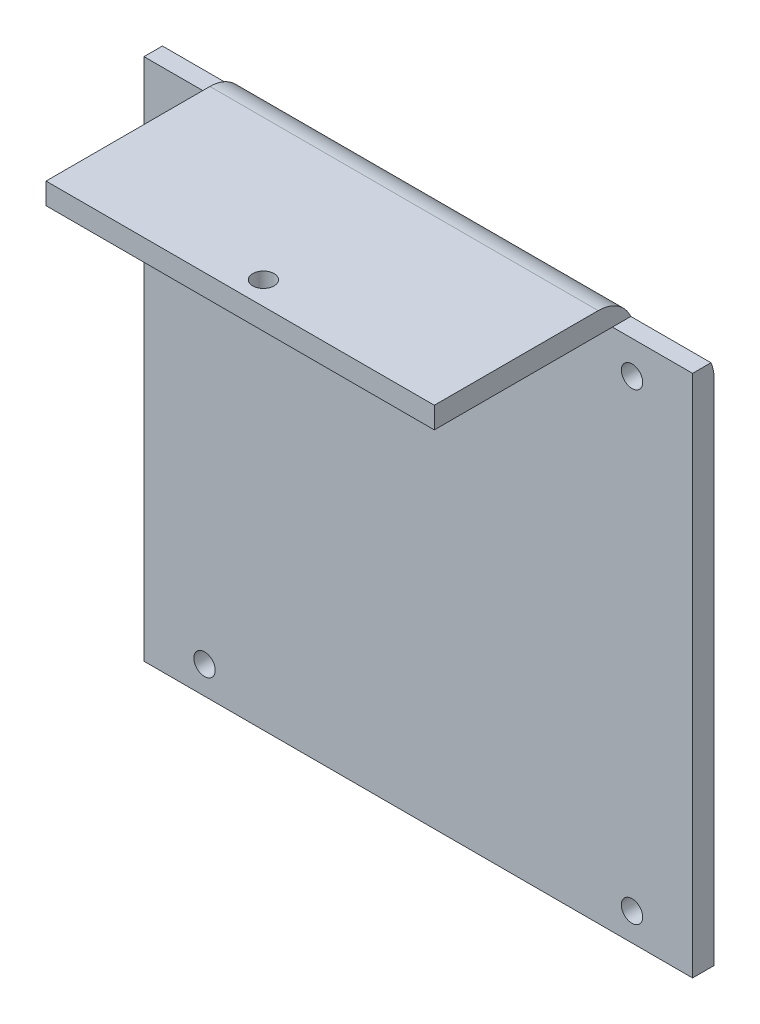
SolidWorks part; units mm, degrees
ref_plane "Plan de face" through (0, 0, 0) normal (0, 0, 1) x (1, 0, 0)
ref_plane "Plan de dessus" through (0, 0, 0) normal (0, 1, 0) x (1, 0, 0)
ref_plane "Plan de droite" through (0, 0, 0) normal (1, 0, 0) x (0, 0, -1)
sketch "Esquisse1" plane through (0, 0, 0) normal (0, 0, 1) x (1, 0, 0)
  line L1 (-38.5, 36.75) -> (38.5, 36.75)
  line L2 (-38.5, 36.75) -> (-38.5, -36.75)
  line L3 (-38.5, -36.75) -> (38.5, -36.75)
  line L4 (38.5, 36.75) -> (38.5, -36.75)
  line L5 (-38.5, 36.75) -> (38.5, -36.75) construction
  line L6 (-38.5, -36.75) -> (38.5, 36.75) construction
  line L7 (30, 32.15) -> (-30, 32.15) construction
  line L8 (30, 32.15) -> (30, -32.85) construction
  line L9 (30, -32.85) -> (-30, -32.85) construction
  line L10 (-30, 32.15) -> (-30, -32.85) construction
  line L11 (30, 32.15) -> (-30, -32.85) construction
  line L12 (30, -32.85) -> (-30, 32.15) construction
  circle A0 centre (30, 32.15) radius 1.5
  circle A1 centre (30, -32.85) radius 1.5
  circle A2 centre (-30, -32.85) radius 1.5
  circle A3 centre (-30, 32.15) radius 1.5
  point P0 (0, 0)
  point P6 (0, 0)
  point P19 (0, -0.35)
  dimension "D3" = 3
  dimension "D1" = 77
  dimension "D2" = 73.5
  dimension "D4" = 65
  dimension "D5" = 60
  dimension "D6" = 3.9
extrude "Boss.-Extru.1" add sketch "Esquisse1" along normal blind 3
sketch "Esquisse9" plane through (0, 36.75, 0) normal (0, 1, 0) x (1, 0, 0)
  line L0 (38.5, 0) -> (-38.5, 0) construction
  line L1 (-27.25, 0) -> (27.25, 0)
  line L2 (-27.25, 0) -> (-27.25, -3)
  line L3 (-27.25, -3) -> (27.25, -3)
  line L4 (27.25, 0) -> (27.25, -3)
  line L5 (38.5, -3) -> (-38.5, -3) construction
  line L6 (-38.5, -3) -> (-38.5, 0) construction
  point P10 (0, 0)
  point P12 (0, 0)
  dimension "D1" = 11.25
sketch "Esquisse45" plane through (0, 36.75, 0) normal (0, 1, 0) x (1, 0, 0)
  line L0 (38.5, 0) -> (-38.5, 0) construction
  line L1 (-27.25, 0) -> (27.25, 0)
  line L2 (-27.25, 0) -> (-27.25, -3)
  line L3 (-27.25, -3) -> (27.25, -3)
  line L4 (27.25, 0) -> (27.25, -3)
  line L5 (38.5, -3) -> (-38.5, -3) construction
  line L6 (-38.5, -3) -> (-38.5, 0) construction
  line L7 (38.5, -3) -> (38.5, 0) construction
  dimension "D1" = 11.25
  dimension "D2" = 11.25
extrude "Boss.-Extru.2" add sketch "Esquisse45" along normal blind 3
sketch "Esquisse46" plane through (0, 0, 3) normal (0, 0, 1) x (1, 0, 0)
  line L1 (-27.25, 39.75) -> (27.25, 39.75)
  line L2 (-27.25, 39.75) -> (-27.25, 36.75)
  line L3 (-27.25, 36.75) -> (27.25, 36.75)
  line L4 (27.25, 39.75) -> (27.25, 36.75)
extrude "Boss.-Extru.3" add sketch "Esquisse46" along normal blind 25
fillet "Congé1" radius 5 1 edges at (0, 39.75, 0)
sketch "Esquisse47" plane through (0, 39.75, 0) normal (0, 1, 0) x (1, 0, 0)
  line L0 (-27.25, -24.7426) -> (27.25, -24.7426) construction
  line L1 (-27.25, -5) -> (-27.25, -28) construction
  line L2 (27.25, -28) -> (27.25, -5) construction
  line L3 (27.25, -5) -> (-27.25, -5) construction
  circle A0 centre (0, -24.7426) radius 1.5
  dimension "D1" = 3
  dimension "D2" = 19.7426
extrude "Enlèv. mat.-Extru.2" cut sketch "Esquisse47" against normal blind 25 contours A0
